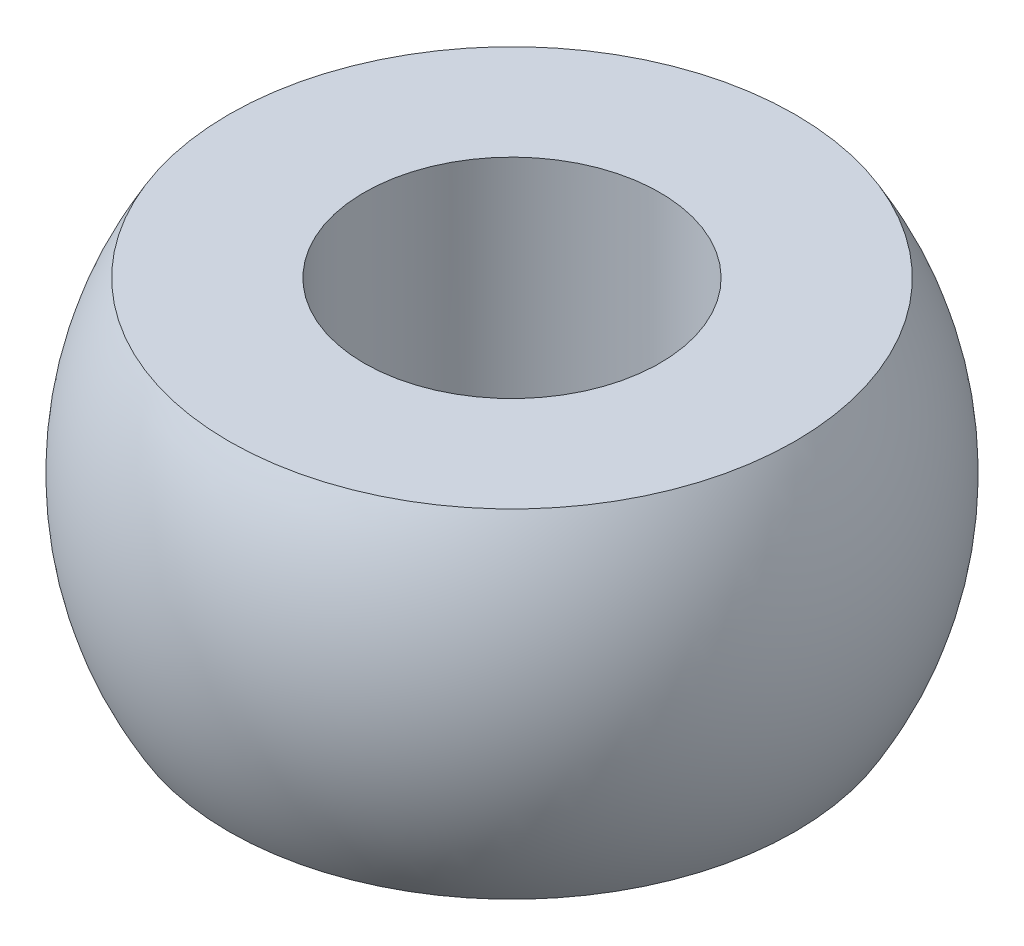
SolidWorks part; units mm, degrees
ref_plane "Front Plane" through (0, 0, 0) normal (0, 0, 1) x (1, 0, 0)
ref_plane "Top Plane" through (0, 0, 0) normal (0, 1, 0) x (1, 0, 0)
ref_plane "Right Plane" through (0, 0, 0) normal (1, 0, 0) x (0, 0, -1)
sketch "Sketch1" plane through (0, 0, 0) normal (1, 0, 0) x (0, 0, -1)
  line L0 (0, 2) -> (0, -2)
  line L1 (0, 2) -> (-3.35, 2)
  line L2 (0, -2) -> (-3.35, -2)
  arc A0 (-3.35, 2) -> (-3.35, -2) centre (0, 0) ccw
  dimension "D1" = 4
  dimension "D2" = 3.35
  dimension "D3" = 2
revolve "Revolve1" add sketch "Sketch1" angle 360 about L0
sketch "Sketch2" plane through (0, 2, 0) normal (0, 1, 0) x (1, 0, 0)
  circle A0 centre (0, 0) radius 1.75
  dimension "D1" = 3.5
extrude "Cut-Extrude1" cut sketch "Sketch2" against normal blind 10
